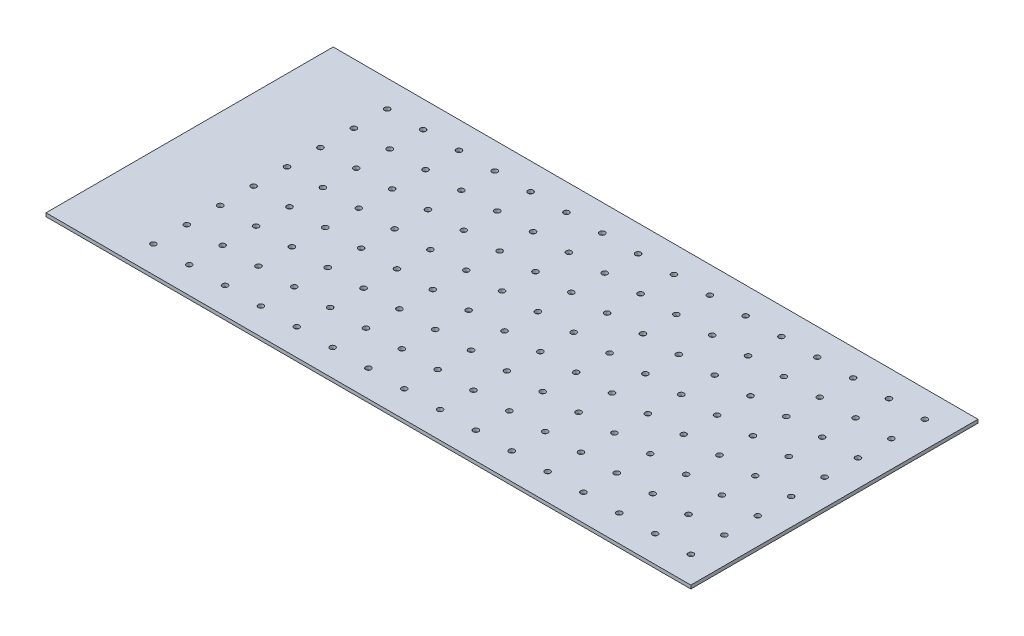
SolidWorks part; units mm, degrees
ref_plane "Front Plane" through (0, 0, 0) normal (0, 0, 1) x (1, 0, 0)
ref_plane "Top Plane" through (0, 0, 0) normal (0, 1, 0) x (1, 0, 0)
ref_plane "Right Plane" through (0, 0, 0) normal (1, 0, 0) x (0, 0, -1)
sketch "Sketch1" plane through (0, 0, 0) normal (0, 1, 0) x (1, 0, 0)
  line L1 (-272.5, 132.5) -> (272.5, 132.5)
  line L2 (-272.5, 132.5) -> (-272.5, -132.5)
  line L3 (-272.5, -132.5) -> (272.5, -132.5)
  line L4 (272.5, 132.5) -> (272.5, -132.5)
  line L5 (-272.5, 132.5) -> (272.5, -132.5) construction
  line L6 (-272.5, -132.5) -> (272.5, 132.5) construction
  point P0 (0, 0)
  dimension "D1" = 265
  dimension "D2" = 545
extrude "Boss-Extrude1" add sketch "Sketch1" along normal blind 3.18
sketch "Sketch4" plane through (0, 3.18, 0) normal (0, 1, 0) x (1, 0, 0)
  line L0 (272.5, 132.5) -> (-272.5, 132.5) construction
  line L1 (-272.5, 132.5) -> (-272.5, -132.5) construction
  circle A0 centre (-248, 107.9) radius 2.5
  dimension "D1" = 24.6
  dimension "D2" = 24.5
  dimension "D3" = 5
extrude "Cut-Extrude1" cut sketch "Sketch4" against normal up to next contours A0
pattern_linear "LPattern1" count 16 spacing 33.0667 along (1, 0, 0) count 8 spacing 30.8286 along (0, 0, 1) of "Cut-Extrude1"
sketch "Sketch5" plane through (-272.5, 0, 0) normal (-1, 0, 0) x (0, 0, 1)
  line L1 (-132.5, 3.18) -> (132.5, 3.18)
  line L2 (-132.5, 3.18) -> (-132.5, 0)
  line L3 (-132.5, 0) -> (132.5, 0)
  line L4 (132.5, 3.18) -> (132.5, 0)
extrude "Boss-Extrude2" add sketch "Sketch5" along normal blind 50
